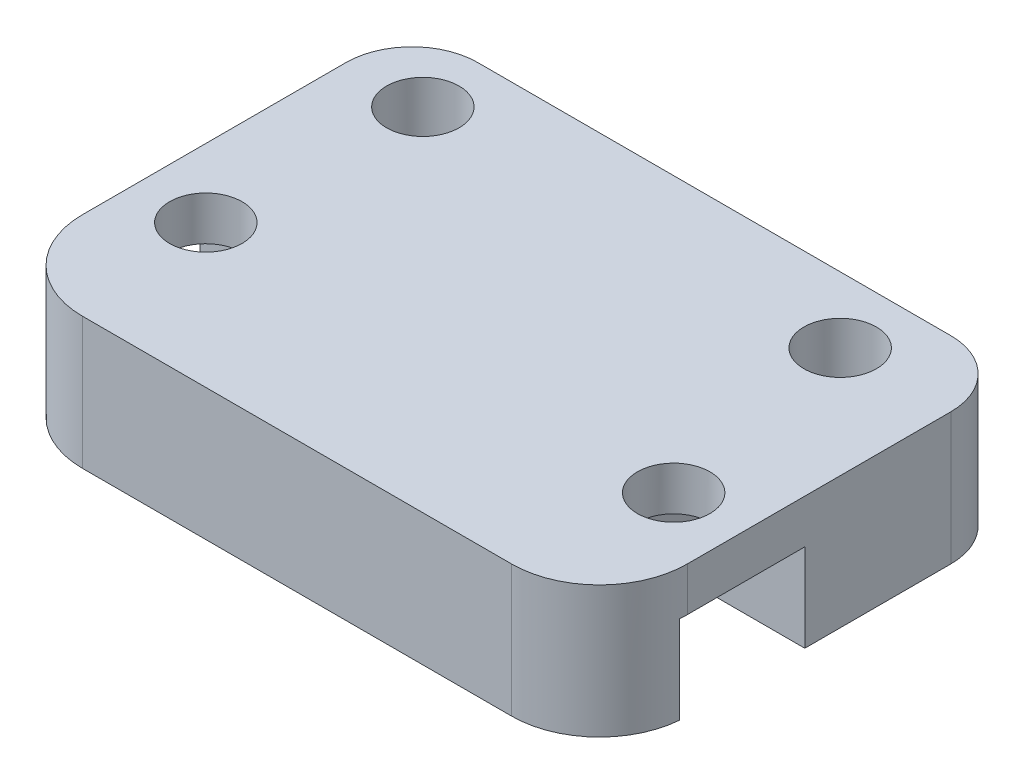
SolidWorks part; units mm, degrees
ref_plane "Front Plane" through (0, 0, 0) normal (0, 0, 1) x (1, 0, 0)
ref_plane "Top Plane" through (0, 0, 0) normal (0, 1, 0) x (1, 0, 0)
ref_plane "Right Plane" through (0, 0, 0) normal (1, 0, 0) x (0, 0, -1)
sketch "Sketch1" plane through (0, 0, 0) normal (0, 0, 1) x (1, 0, 0)
  line L0 (0, 4) -> (0, 0) construction
  line L1 (-13.77, -3) -> (13.77, -3)
  line L2 (-13.77, -3) -> (-13.77, 3)
  line L3 (-13.77, 3) -> (13.77, 3)
  line L4 (13.77, -3) -> (13.77, 3)
  line L5 (-13.77, -3) -> (13.77, 3) construction
  line L6 (-13.77, 3) -> (13.77, -3) construction
  circle A0 centre (0, 4) radius 7.6 construction
  point P0 (0, 0)
  dimension "D3" = 15.2
  dimension "D1" = 7
  dimension "D2" = 1
  dimension "D4" = 27.54
extrude "Boss-Extrude1" add sketch "Sketch1" along normal blind 13 contours A0 L3 L2 L1 L4
sketch "Sketch2" plane through (0, 3, 0) normal (0, 1, 0) x (1, 0, 0)
  line L0 (13.77, 0) -> (7.53, -13) construction
  line L1 (-13.77, 0) -> (-7.53, -13) construction
  line L2 (-13.77, -13) -> (13.77, -13) construction
  line L3 (-13.77, -13) -> (-7.53, -13) construction
  line L4 (7.53, -13) -> (13.77, -13) construction
  line L5 (13.77, -13) -> (13.77, 0) construction
  circle A0 centre (-10.65, -6.5) radius 1.65
  circle A1 centre (10.65, -6.5) radius 1.65
  dimension "D1" = 3.3
  dimension "D2" = 3.12
extrude "Cut-Extrude1" cut sketch "Sketch2" against normal through all
sketch "Sketch4" plane through (0, 0, 0) normal (0, 0, -1) x (-1, 0, 0)
  line L8 (-13.77, -3) -> (13.77, -3)
  line L9 (13.77, -3) -> (13.77, 3)
  line L10 (13.77, 3) -> (-13.77, 3)
  line L11 (-13.77, 3) -> (-13.77, -3)
  line L12 (-13.77, -3) -> (13.77, -3)
  line L13 (13.77, -3) -> (13.77, 3)
  line L14 (13.77, 3) -> (-13.77, 3)
  line L15 (-13.77, 3) -> (-13.77, -3)
  dimension "D1" = 0
extrude "Boss-Extrude2" add sketch "Sketch4" along normal blind 6
sketch "Sketch3" plane through (0, -3, 0) normal (0, -1, 0) x (1, 0, 0)
  line L0 (8.73, -3) -> (-10.27, -3) construction
  line L1 (13.77, -6) -> (-13.77, -6) construction
  line L2 (-13.77, 13) -> (-13.77, -6) construction
  arc A2 (7.13, 1) -> (10.33, 1) centre (8.73, -3) ccw construction
  arc A3 (-11.6208, 1) -> (-8.8261, 0.9674) centre (-10.27, -3) ccw construction
  circle A4 centre (8.73, -3) radius 1.65
  circle A5 centre (-10.27, -3) radius 1.65
  dimension "D1" = 3.3
  dimension "D2" = 19
  dimension "D3" = 3
  dimension "D4" = 3.5
fillet "Fillet1" radius 4 2 edges at (13.77, 0, 13) (-13.77, 0, 13)
fillet "Fillet2" radius 3 2 edges at (13.77, 0, -6) (-13.77, 0, -6)
extrude "Cut-Extrude2" cut sketch "Sketch3" against normal through all both and the other way through all
sketch "Sketch6" plane through (0, -3, 0) normal (0, -1, 0) x (1, 0, 0)
  line L0 (12.2954, 9.35) -> (15.2954, 9.35)
  line L1 (13.9409, 6.5) -> (12.2954, 9.35) construction
  line L2 (12.2954, 9.35) -> (9.0046, 9.35)
  line L3 (9.0046, 9.35) -> (7.3591, 6.5)
  line L4 (7.3591, 6.5) -> (9.0046, 3.65)
  line L5 (9.0046, 3.65) -> (12.2954, 3.65)
  line L6 (12.2954, 3.65) -> (13.9409, 6.5) construction
  line L7 (-13.9409, 6.5) -> (-12.2954, 3.65) construction
  line L8 (-12.2954, 3.65) -> (-9.0046, 3.65)
  line L9 (-9.0046, 3.65) -> (-7.3591, 6.5)
  line L10 (-7.3591, 6.5) -> (-9.0046, 9.35)
  line L11 (-9.0046, 9.35) -> (-12.2954, 9.35)
  line L12 (-12.2954, 9.35) -> (-13.9409, 6.5) construction
  line L13 (15.2954, 9.35) -> (15.2954, 3.65)
  line L14 (15.2954, 3.65) -> (12.2954, 3.65)
  line L15 (-12.2954, 9.35) -> (-15.2954, 9.35)
  line L16 (-15.2954, 9.35) -> (-15.2954, 3.65)
  line L17 (-15.2954, 3.65) -> (-12.2954, 3.65)
  circle A1 centre (10.65, 6.5) radius 2.85 construction
  circle A2 centre (-10.65, 6.5) radius 2.85 construction
  dimension "D1" = 5.7
  dimension "D2" = 3
extrude "Cut-Extrude3" cut sketch "Sketch6" against normal blind 4
